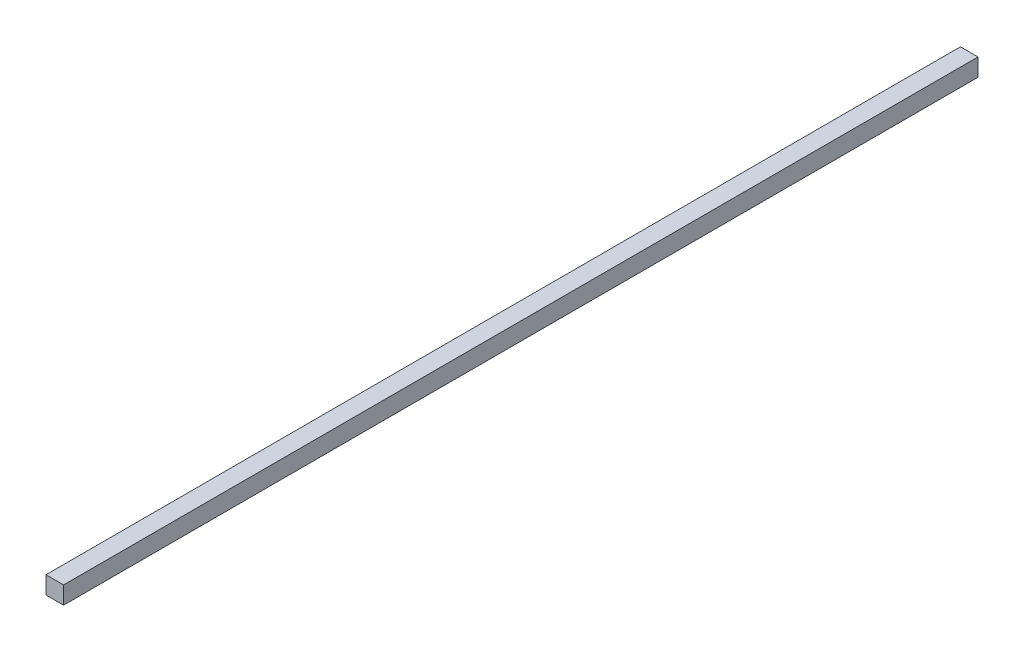
SolidWorks part; units mm, degrees
ref_plane "Front Plane" through (0, 0, 0) normal (0, 0, 1) x (1, 0, 0)
ref_plane "Top Plane" through (0, 0, 0) normal (0, 1, 0) x (1, 0, 0)
ref_plane "Right Plane" through (0, 0, 0) normal (1, 0, 0) x (0, 0, -1)
sketch "Sketch2" plane through (0, 0, 0) normal (0, 1, 0) x (1, 0, 0)
  line L1 (0, 0) -> (6.35, 0)
  line L2 (0, 0) -> (0, 330.2)
  line L3 (0, 330.2) -> (6.35, 330.2)
  line L4 (6.35, 0) -> (6.35, 330.2)
  dimension "D1" = 330.2
  dimension "D2" = 6.35
extrude "Boss-Extrude1" add sketch "Sketch2" along normal blind 6.35
